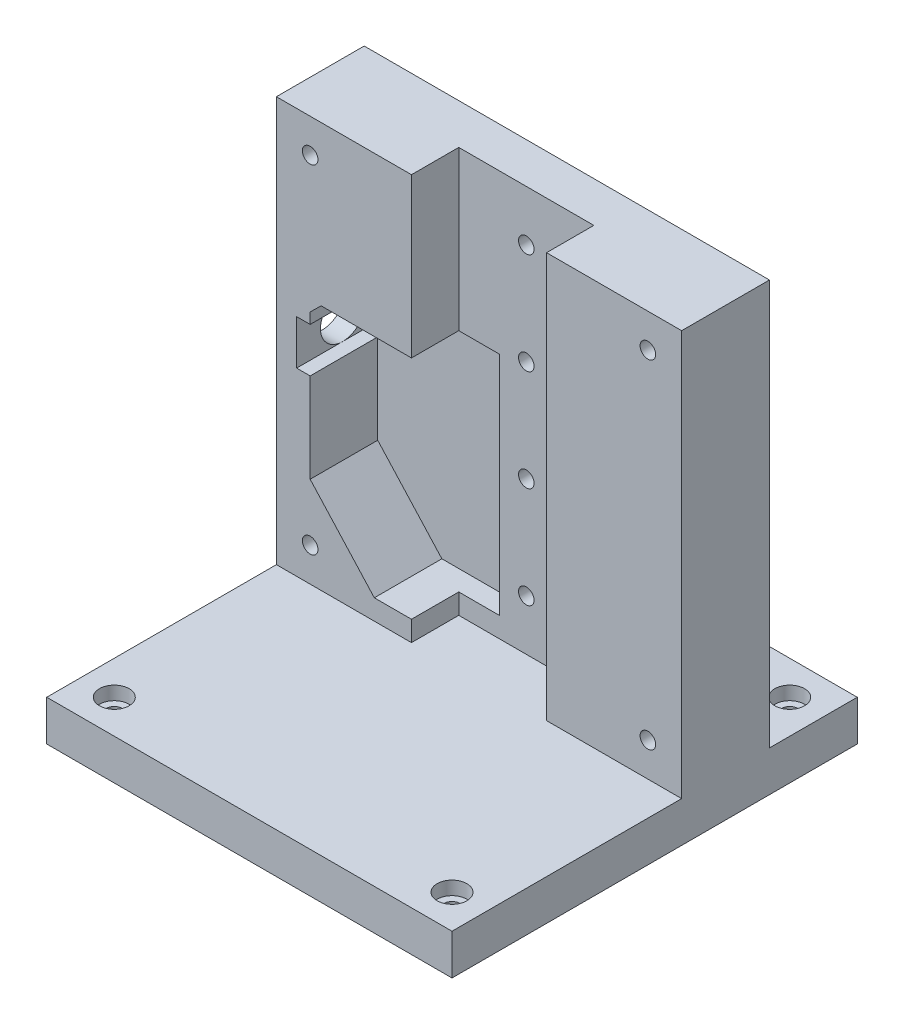
SolidWorks part; units mm, degrees
ref_plane "Front Plane" through (0, 0, 0) normal (0, 0, 1) x (1, 0, 0)
ref_plane "Top Plane" through (0, 0, 0) normal (0, 1, 0) x (1, 0, 0)
ref_plane "Right Plane" through (0, 0, 0) normal (1, 0, 0) x (0, 0, -1)
sketch "Sketch1" plane through (0, 0, 0) normal (0, 0, 1) x (1, 0, 0)
  line L1 (-30, 30) -> (30, 30)
  line L2 (-30, 30) -> (-30, -30)
  line L3 (-30, -30) -> (30, -30)
  line L4 (30, 30) -> (30, -30)
  line L5 (-30, 30) -> (30, -30) construction
  line L6 (-30, -30) -> (30, 30) construction
  point P0 (0, 0)
  dimension "D1" = 60
  dimension "D2" = 60
extrude "Boss-Extrude1" add sketch "Sketch1" along normal blind 6
sketch "Sketch2" plane through (0, 0, 0) normal (0, 0, -1) x (-1, 0, 0)
  line L0 (0, -30) -> (0, 30)
  line L1 (30, -30) -> (-30, -30) construction
  line L2 (-30, 30) -> (30, 30) construction
  circle A0 centre (0, 22.5) radius 1.15
  circle A4 centre (0, -22.5) radius 1.15
  circle A5 centre (0, -7.5) radius 1.15
  circle A6 centre (0, 7.5) radius 1.15
  dimension "D1" = 2.3
  dimension "D2" = 15
  dimension "D3" = 15
  dimension "D4" = 15
sketch "Sketch3" plane through (0, 0, 0) normal (0, 0, -1) x (-1, 0, 0)
  line L7 (2.1, 6.2876) -> (2.1, 8.7124)
  line L8 (2.1, 8.7124) -> (0, 9.9249)
  line L9 (0, 9.9249) -> (-2.1, 8.7124)
  line L10 (-2.1, 8.7124) -> (-2.1, 6.2876)
  line L11 (-2.1, 6.2876) -> (0, 5.0751)
  line L12 (0, 5.0751) -> (2.1, 6.2876)
  line L13 (2.1, -8.7124) -> (2.1, -6.2876)
  line L14 (2.1, -6.2876) -> (0, -5.0751)
  line L15 (0, -5.0751) -> (-2.1, -6.2876)
  line L16 (-2.1, -6.2876) -> (-2.1, -8.7124)
  line L17 (-2.1, -8.7124) -> (0, -9.9249)
  line L18 (0, -9.9249) -> (2.1, -8.7124)
  line L19 (2.1, -23.7124) -> (2.1, -21.2876)
  line L20 (2.1, -21.2876) -> (0, -20.0751)
  line L21 (0, -20.0751) -> (-2.1, -21.2876)
  line L22 (-2.1, -21.2876) -> (-2.1, -23.7124)
  line L23 (-2.1, -23.7124) -> (0, -24.9249)
  line L24 (0, -24.9249) -> (2.1, -23.7124)
  line L27 (0, 20.0751) -> (2.1, 21.2876)
  line L28 (2.1, 21.2876) -> (2.1, 23.7124)
  line L29 (2.1, 23.7124) -> (0, 24.9249)
  line L30 (0, 24.9249) -> (-2.1, 23.7124)
  line L31 (-2.1, 23.7124) -> (-2.1, 21.2876)
  line L32 (-2.1, 21.2876) -> (0, 20.0751)
  circle A0 centre (0, 22.5) radius 2.1 construction
  circle A1 centre (0, 7.5) radius 2.1 construction
  circle A2 centre (0, -7.5) radius 2.1 construction
  circle A3 centre (0, -22.5) radius 2.1 construction
extrude "Cut-Extrude2" cut sketch "Sketch3" against normal blind 3
sketch "Sketch12" plane through (0, 0, 0) normal (0, 0, -1) x (-1, 0, 0)
  circle A0 centre (0, 22.5) radius 1.15
  circle A1 centre (0, 7.5) radius 1.15
  circle A2 centre (0, -7.5) radius 1.15
  circle A3 centre (0, -22.5) radius 1.15
extrude "Cut-Extrude9" cut sketch "Sketch12" against normal through all
sketch "Sketch4" plane through (0, 0, 6) normal (0, 0, 1) x (1, 0, 0)
  line L0 (0, -30) -> (-4, -30)
  line L1 (-30, -30) -> (30, -30) construction
  line L2 (-4, -30) -> (-4, -27)
  line L5 (30, 30) -> (-30, 30) construction
  line L6 (-4, 30) -> (-4, 6.5)
  dimension "D1" = 4
  dimension "D2" = 3
sketch "Sketch5" plane through (0, 0, 6) normal (0, 0, 1) x (1, 0, 0)
  line L3 (-30, -30) -> (30, -30) construction
  line L4 (-10, 30) -> (10, 30)
  line L5 (-10, 30) -> (-10, -30)
  line L6 (-10, -30) -> (10, -30)
  line L7 (10, 30) -> (10, -30)
  line L8 (-10, 30) -> (10, -30) construction
  line L9 (-10, -30) -> (10, 30) construction
  line L11 (-30, 30) -> (30, 30)
  line L12 (-30, 30) -> (-30, -30)
  line L13 (-30, -30) -> (30, -30)
  line L14 (30, 30) -> (30, -30)
  line L15 (-30, 30) -> (30, -30) construction
  line L16 (-30, -30) -> (30, 30) construction
  point P6 (0, 0)
  point P14 (0, 0)
  line M5 (30, -30) -> (30, 30)
  line M6 (30, 30) -> (-30, 30)
  line M7 (-30, 30) -> (-30, -30)
  line M8 (-30, -30) -> (30, -30)
extrude "Boss-Extrude2" add sketch "Sketch5" along normal blind 7 contours L5 M6 M7 M8 | L7 M6 M8 M5
sketch "Sketch6" plane through (0, 0, 13) normal (0, 0, 1) x (1, 0, 0)
  line L2 (-20, -20) -> (20, -20)
  line L3 (-20, -20) -> (-20, 20)
  line L4 (-20, 20) -> (20, 20)
  line L5 (20, -20) -> (20, 20)
  line L6 (-20, -20) -> (20, 20) construction
  line L7 (-20, 20) -> (20, -20) construction
  line L8 (20, -20) -> (30, -20)
  line L9 (20, -20) -> (20, -30)
  line L10 (20, -30) -> (30, -30)
  line L11 (30, -20) -> (30, -30)
  line L12 (-20, -20) -> (-30, -20)
  line L13 (-20, -20) -> (-20, -30)
  line L14 (-20, -30) -> (-30, -30)
  line L15 (-30, -20) -> (-30, -30)
  line L16 (-20, 20) -> (-20, 30)
  line L17 (-20, 20) -> (-30, 20)
  line L18 (-30, 20) -> (-30, 30)
  line L19 (-20, 30) -> (-30, 30)
  line L20 (20, 20) -> (30, 20)
  line L21 (20, 20) -> (20, 30)
  line L22 (20, 30) -> (30, 30)
  line L23 (30, 20) -> (30, 30)
  circle A0 centre (25, -25) radius 2.2
  circle A1 centre (25, -25) radius 1.15
  circle A2 centre (-25, -25) radius 2.2
  circle A3 centre (-25, -25) radius 1.15
  circle A4 centre (-25, 25) radius 2.2
  circle A5 centre (-25, 25) radius 1.15
  circle A6 centre (25, 25) radius 2.2
  circle A7 centre (25, 25) radius 1.15
  point P4 (0, 0)
  point P39 (0, 0)
  dimension "D3" = 4
  dimension "D1" = 40
  dimension "D2" = 40
extrude "Cut-Extrude4" cut sketch "Sketch6" against normal through all contours A5 | A7 | A1 | A3
sketch "Sketch9" plane through (0, 0, 13) normal (0, 0, 1) x (1, 0, 0)
  line L0 (-10, -30) -> (-10, -27)
  line L1 (-10, 30) -> (-10, -30) construction
  line L2 (-30, 30) -> (-30, -30) construction
  line L3 (-20, -20) -> (-30, -20)
  line L4 (-20, -20) -> (-20, -30)
  line L5 (-20, -30) -> (-30, -30)
  line L6 (-30, -20) -> (-30, -30)
  line L7 (-20, -20) -> (-30, -30) construction
  line L8 (-20, -30) -> (-30, -20) construction
  line L9 (-33, 3.3) -> (-27, 3.3)
  line L10 (-33, 3.3) -> (-33, -3.3)
  line L11 (-33, -3.3) -> (-27, -3.3)
  line L12 (-27, 3.3) -> (-27, -3.3)
  line L13 (-33, 3.3) -> (-27, -3.3) construction
  line L14 (-33, -3.3) -> (-27, 3.3) construction
  line L15 (-27, 3.3) -> (-25, 3.3)
  line L16 (-10, 6.5) -> (-27, 6.5)
  line L17 (-10, 6.5) -> (-10, -27)
  line L18 (-10, -27) -> (-27, -27)
  line L19 (-27, 6.5) -> (-27, -27)
  line L20 (-27, -3.3) -> (-25, -3.3)
  line L21 (-25, 3.3) -> (-25, 6.5)
  line L22 (-25, -3.3) -> (-25, -20)
  line L23 (-25, 4.9) -> (-21.75, 4.9)
  line L24 (-22.5, -22.5) -> (-20, -20)
  line L25 (-25, -16.55) -> (-15.5, -27)
  line L29 (-25, 6.5) -> (-24.3375, 6.5)
  line L36 (-23.375, 6.5) -> (-25, 4.9)
  line L37 (-25, 4.9) -> (-25, 3.3)
  line L38 (-27, 3.3) -> (-25, 3.3)
  point P5 (-25, -25)
  point P12 (-30, 0)
  point P30 (-25, 4.9)
  dimension "D1" = 3
  dimension "D2" = 6
  dimension "D3" = 6.6
  dimension "D4" = 2
  dimension "D5" = 2
  dimension "D6" = 3.25
extrude "Cut-Extrude6" cut sketch "Sketch9" against normal blind 10
sketch "Sketch10" plane through (0, 0, 6) normal (0, 0, 1) x (1, 0, 0)
  line L1 (-10, -27) -> (-4, -27)
  line L2 (-10, -27) -> (-10, 6.5)
  line L3 (-10, 6.5) -> (-4, 6.5)
  line L4 (-4, -27) -> (-4, 6.5)
extrude "Cut-Extrude7" cut sketch "Sketch10" against normal blind 3
sketch "Sketch11" plane through (-27, 0, 0) normal (1, 0, 0) x (0, 0, -1)
  line L0 (-3, 3.3) -> (-3, -3.3)
  line L1 (-3, 3.3) -> (-3, -3.3) construction
  circle A0 centre (-6.175, 0) radius 3.3
extrude "Cut-Extrude8" cut sketch "Sketch11" against normal through all contours L0 A0
sketch "Sketch13" plane through (0, -30, 0) normal (0, -1, 0) x (-1, 0, 0)
  line L0 (10, -6) -> (-10, -6) construction
  line L1 (30, -47) -> (-30, -47)
  line L2 (30, -47) -> (30, 13)
  line L3 (30, 13) -> (-30, 13)
  line L4 (-30, -47) -> (-30, 13)
  line L5 (30, -47) -> (-30, 13) construction
  line L6 (30, 13) -> (-30, -47) construction
  point P0 (0, -17)
  dimension "D1" = 11
  dimension "D2" = 60
extrude "Boss-Extrude3" add sketch "Sketch13" along normal blind 6
sketch "Sketch14" plane through (0, -30, 0) normal (0, 1, 0) x (1, 0, 0)
  line L0 (20, -37) -> (30, -47)
  line L1 (30, -47) -> (20, -47)
  line L2 (30, -47) -> (30, -37)
  line L3 (30, -37) -> (20, -37)
  line L4 (20, -47) -> (20, -37)
  line L5 (-30, 13) -> (30, -47)
  circle A0 centre (25, -42) radius 1.15
  circle A1 centre (-25, -42) radius 1.15
  circle A2 centre (-25, 8) radius 1.15
  circle A3 centre (25, 8) radius 1.15
  point P8 (0, -17)
  point P19 (0, -17)
  dimension "D3" = 4
  dimension "D1" = 10
  dimension "D2" = 10
extrude "Cut-Extrude10" cut sketch "Sketch14" against normal through all contours L5 A2 | L5 A2 | A3 | L5 A0 | L5 A0 | A1
sketch "Sketch15" plane through (0, -30, 0) normal (0, 1, 0) x (1, 0, 0)
  line L0 (25, -42) -> (-25, 8)
  circle A0 centre (25, -42) radius 2.2
  circle A1 centre (-25, -42) radius 2.2
  circle A2 centre (-25, 8) radius 2.2
  circle A3 centre (25, 8) radius 2.2
  point P5 (0, -17)
  point P15 (0, -17)
  dimension "D1" = 4
extrude "Cut-Extrude11" cut sketch "Sketch15" against normal blind 2
